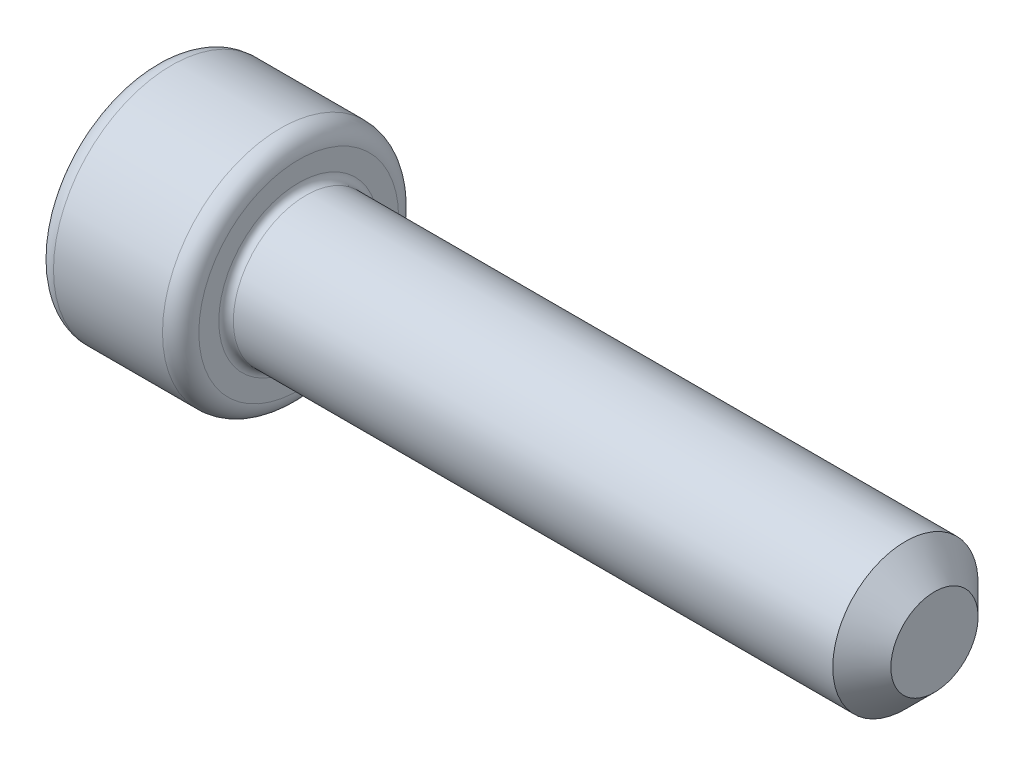
SolidWorks part; units mm, degrees
material "Простая углеродистая сталь"
ref_plane "Front" through (0, 0, 0) normal (0, 0, 1) x (1, 0, 0)
ref_plane "Top" through (0, 0, 0) normal (0, 1, 0) x (1, 0, 0)
ref_plane "Right" through (0, 0, 0) normal (1, 0, 0) x (0, 0, -1)
sketch "Эскиз1" plane through (0, 0, 0) normal (0, 0, 1) x (1, 0, 0)
  line L0 (-7.6495, 0) -> (49.0592, 0) construction
  line L1 (0, 0) -> (0, 5.5)
  line L2 (1, 6.5) -> (7, 6.5)
  line L3 (8, 5.5) -> (8, 4.4)
  line L4 (8.4, 4) -> (41.4, 4)
  line L5 (43, 2.4) -> (43, 0)
  line L6 (43, 0) -> (0, 0)
  line L7 (41.4, 4) -> (43, 2.4)
  arc A0 (8, 4.4) -> (8.4, 4) centre (8.4, 4.4) ccw
  arc A1 (7, 6.5) -> (8, 5.5) centre (7, 5.5) cw
  arc A2 (0, 5.5) -> (1, 6.5) centre (1, 5.5) cw
  point P8 (43, 4)
  point P17 (8, 6.5)
  point P20 (0, 6.5)
  dimension "D7" = 0.4
  dimension "D8" = 1
  dimension "D1" = 1.6
  dimension "D2" = 45
  dimension "D3" = 8
  dimension "D4" = 35
  dimension "D5" = 13
  dimension "D6" = 8
revolve "Повернуть1" add sketch "Эскиз1" angle 360 about L0
cosmetic thread "Условное изображение резьбы1" parameters "D2"=6.619
sketch "Эскиз2" plane through (0, 0, 0) normal (-1, 0, 0) x (0, 0, 1)
  line L1 (0, 3.4641) -> (-3, 1.7321)
  line L2 (-3, 1.7321) -> (-3, -1.7321)
  line L3 (-3, -1.7321) -> (0, -3.4641)
  line L4 (0, -3.4641) -> (3, -1.7321)
  line L5 (3, -1.7321) -> (3, 1.7321)
  line L6 (3, 1.7321) -> (0, 3.4641)
  circle A0 centre (0, 0) radius 3 construction
  dimension "D1" = 6
extrude "Вырез-Вытянуть1" cut sketch "Эскиз2" against normal blind 4
sketch "Эскиз3" plane through (0, 0, 0) normal (-1, 0, 0) x (0, 0, 1)
  circle A0 centre (0, 0) radius 3.6
  dimension "D1" = 7.2
extrude "Вырез-Вытянуть2" cut sketch "Эскиз3" against normal through all draft 60
